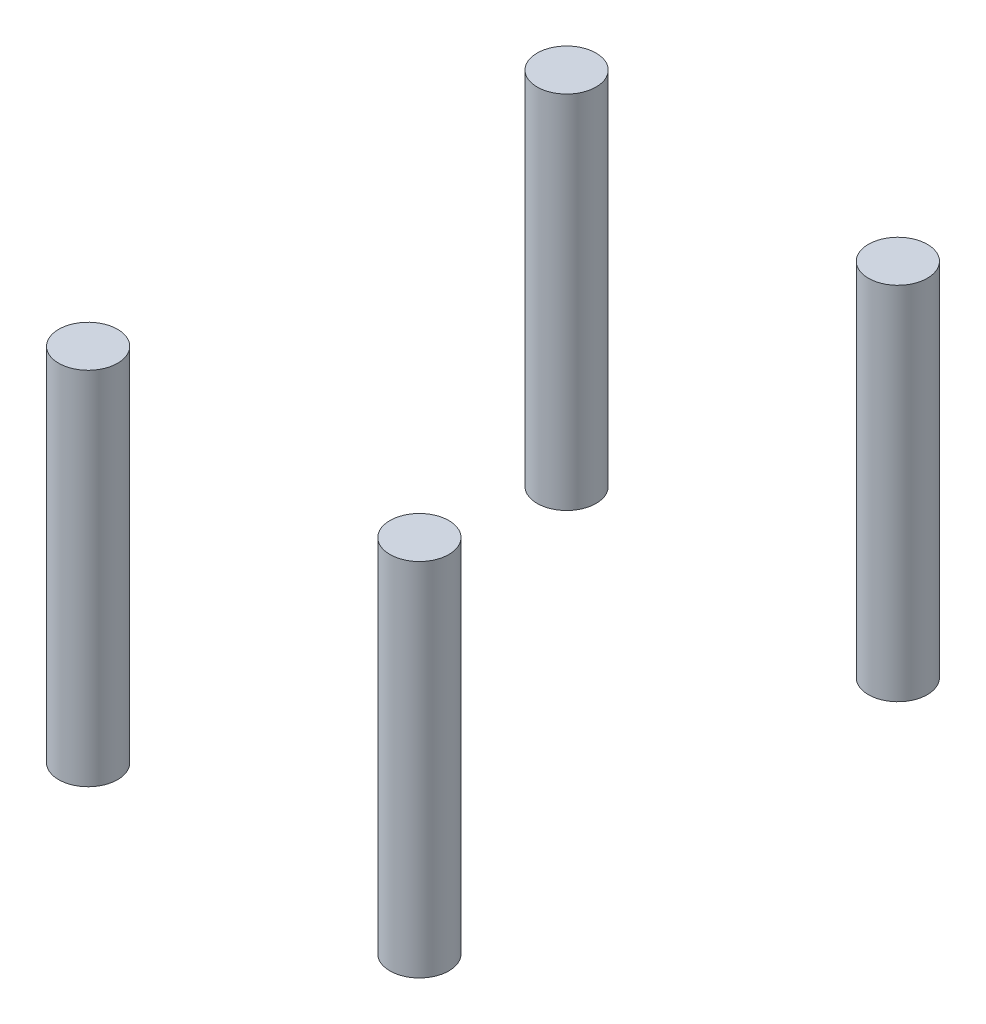
SolidWorks part; units mm, degrees
ref_plane "Front Plane" through (0, 0, 0) normal (0, 0, 1) x (1, 0, 0)
ref_plane "Top Plane" through (0, 0, 0) normal (0, 1, 0) x (1, 0, 0)
ref_plane "Right Plane" through (0, 0, 0) normal (1, 0, 0) x (0, 0, -1)
sketch "Sketch1" plane through (0, 0, 0) normal (0, 1, 0) x (1, 0, 0)
  line L0 (0, -55) -> (0, 55) construction
  line L1 (-82.5, 37.5) -> (82.5, 37.5)
  line L2 (-82.5, 37.5) -> (-82.5, -37.5)
  line L3 (-82.5, -37.5) -> (82.5, -37.5)
  line L4 (82.5, 37.5) -> (82.5, -37.5)
  line L5 (-82.5, 37.5) -> (82.5, -37.5) construction
  line L6 (-82.5, -37.5) -> (82.5, 37.5) construction
  circle A0 centre (22.5, 32.5) radius 4
  circle A1 centre (22.5, -32.5) radius 4
  circle A2 centre (-22.5, -32.5) radius 4
  circle A3 centre (-22.5, 32.5) radius 4
  point P0 (0, 0)
  dimension "D3" = 8
  dimension "D1" = 165
  dimension "D2" = 75
  dimension "D4" = 60
  dimension "D5" = 5
  dimension "D6" = 5
extrude "Boss-Extrude1" add sketch "Sketch1" along normal blind 49 contours A1 | A0 | A3 | A2
